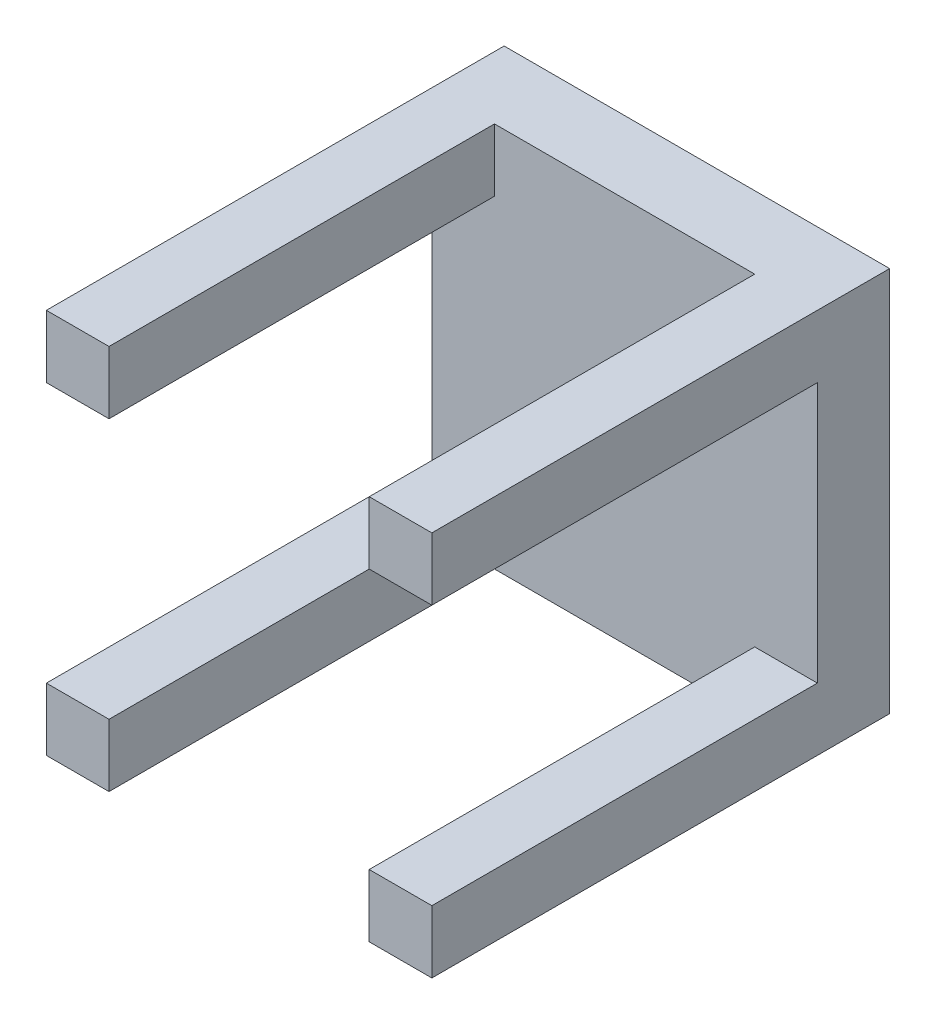
SolidWorks part; units mm, degrees
ref_plane "前视基准面" through (0, 0, 0) normal (0, 0, 1) x (1, 0, 0)
ref_plane "上视基准面" through (0, 0, 0) normal (0, 1, 0) x (1, 0, 0)
ref_plane "右视基准面" through (0, 0, 0) normal (1, 0, 0) x (0, 0, -1)
sketch "草图1" plane through (0, 0, 0) normal (0, 0, 1) x (1, 0, 0)
  line L1 (-40, 40) -> (40, 40)
  line L2 (-40, 40) -> (-40, -40)
  line L3 (-40, -40) -> (40, -40)
  line L4 (40, 40) -> (40, -40)
  line L5 (-40, 40) -> (40, -40) construction
  line L6 (-40, -40) -> (40, 40) construction
  line L7 (-40, 40) -> (-25.1508, 40)
  line L8 (-40, 40) -> (-40, 25.1508)
  line L9 (-40, 25.1508) -> (-25.1508, 25.1508)
  line L10 (-25.1508, 40) -> (-25.1508, 25.1508)
  line L11 (40, 40) -> (25.1508, 40)
  line L12 (40, 40) -> (40, 25.1508)
  line L13 (40, 25.1508) -> (25.1508, 25.1508)
  line L14 (25.1508, 40) -> (25.1508, 25.1508)
  line L15 (-40, -40) -> (-25.9029, -40)
  line L16 (-40, -40) -> (-40, -54.0971)
  line L19 (40, -40) -> (39.6216, -40)
  line L20 (40, -40) -> (40, -39.6216)
  line L23 (-40, -40) -> (-25.1508, -40)
  line L24 (-40, -40) -> (-40, -25.1508)
  line L25 (-40, -25.1508) -> (-25.1508, -25.1508)
  line L26 (-25.1508, -40) -> (-25.1508, -25.1508)
  line L27 (40, -40) -> (25.1508, -40)
  line L28 (40, -40) -> (40, -25.1508)
  line L29 (40, -25.1508) -> (25.1508, -25.1508)
  line L30 (25.1508, -40) -> (25.1508, -25.1508)
  point P0 (0, 0)
  dimension "D1" = 80
  dimension "D2" = 80
  dimension "D3" = 21
  dimension "D4" = 21
  dimension "D5" = 21
  dimension "D6" = 21
extrude "凸台-拉伸6" add sketch "草图1" along normal blind 15 contours L10 L1 L2 L9 | L3 L30 L29 L4 L13 L14 L1 L10 L9 L2 L25 L26 | L1 L14 L13 L4 | L30 L3 L4 L29 | L3 L26 L25 L2
sketch "草图4" plane through (0, 0, 15) normal (0, 0, 1) x (1, 0, 0)
  line L1 (-40, 40) -> (-27, 40)
  line L2 (-40, 40) -> (-40, 27)
  line L3 (-40, 27) -> (-27, 27)
  line L4 (-27, 40) -> (-27, 27)
  line L5 (40, 40) -> (27, 40)
  line L6 (40, 40) -> (40, 27)
  line L7 (40, 27) -> (27, 27)
  line L8 (27, 40) -> (27, 27)
  line L9 (-40, -40) -> (-27, -40)
  line L10 (-40, -40) -> (-40, -27)
  line L11 (-40, -27) -> (-27, -27)
  line L12 (-27, -40) -> (-27, -27)
  line L13 (40, -40) -> (27, -40)
  line L14 (40, -40) -> (40, -27)
  line L15 (40, -27) -> (27, -27)
  line L16 (27, -40) -> (27, -27)
  dimension "D1" = 13
  dimension "D2" = 13
  dimension "D3" = 13
  dimension "D4" = 13
  dimension "D5" = 13
  dimension "D6" = 13
  dimension "D7" = 13
  dimension "D8" = 13
extrude "凸台-拉伸7" add sketch "草图4" along normal blind 80
